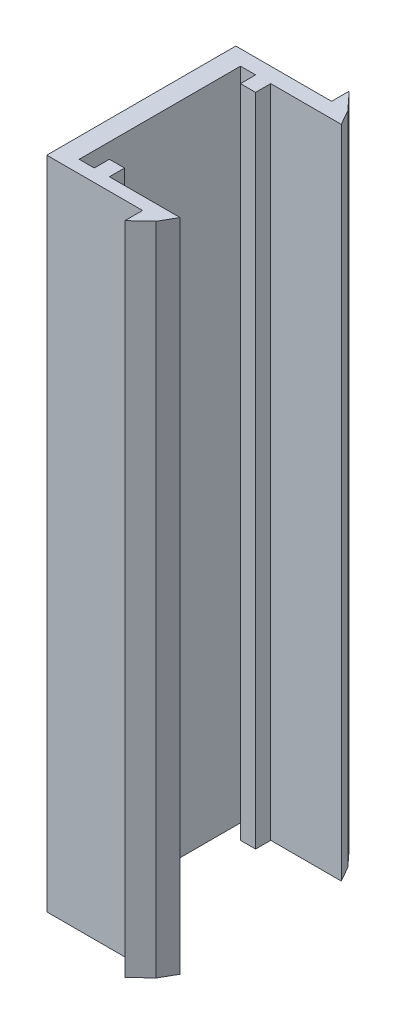
SolidWorks part; units mm, degrees
ref_plane "Front" through (0, 0, 0) normal (0, 0, 1) x (1, 0, 0)
ref_plane "Top" through (0, 0, 0) normal (0, 1, 0) x (1, 0, 0)
ref_plane "Right" through (0, 0, 0) normal (1, 0, 0) x (0, 0, -1)
sketch "Sketch1" plane through (0, 0, 0) normal (0, 1, 0) x (1, 0, 0)
  line L0 (0, -3) -> (0, 29)
  line L1 (0, -3) -> (3, -3)
  line L2 (3, -3) -> (3, 0)
  line L3 (3, 0) -> (6, 0)
  line L4 (6, 0) -> (6, -3)
  line L5 (6, -3) -> (20, -3)
  line L6 (0, 29) -> (3, 29)
  line L7 (-3.9246, -5.5) -> (-3.9246, 32)
  line L8 (-3.9246, 32) -> (15.0754, 32)
  line L9 (-3.9246, -5.5) -> (15.0754, -5.5)
  line L10 (15.0754, 32) -> (15.0754, 35.5)
  line L11 (3, 29) -> (3, 26)
  line L12 (3, 26) -> (6, 26)
  line L13 (6, 26) -> (6, 29)
  line L14 (6, 29) -> (20, 29)
  line L15 (15.0754, 35.5) -> (18.2906, 32)
  line L19 (15.0754, -5.5) -> (15.0754, -9)
  line L20 (15.0754, -9) -> (18.2906, -6)
  line L21 (18.2906, -6) -> (20, -3)
  line L22 (18.2906, 32) -> (20, 29)
  dimension "D1" = 14
extrude "Boss-Extrude2" add sketch "Sketch1" along normal blind 130
sketch "Sketch3" plane through (0, 130, 0) normal (0, 1, 0) x (1, 0, 0)
  line L0 (8.0754, 31) -> (8.0754, -7)
  line L1 (8.0754, 31) -> (-3, 31) construction
  line L2 (8.0754, -7) -> (18.2906, -6)
  line L3 (18.2906, -6) -> (20, -3)
  line L4 (20, -3) -> (20, 29)
  line L5 (20, 29) -> (11.2906, 32)
  line L6 (11.2906, 32) -> (8.0754, 33)
  line L7 (8.0754, 33) -> (8.0754, 31)
